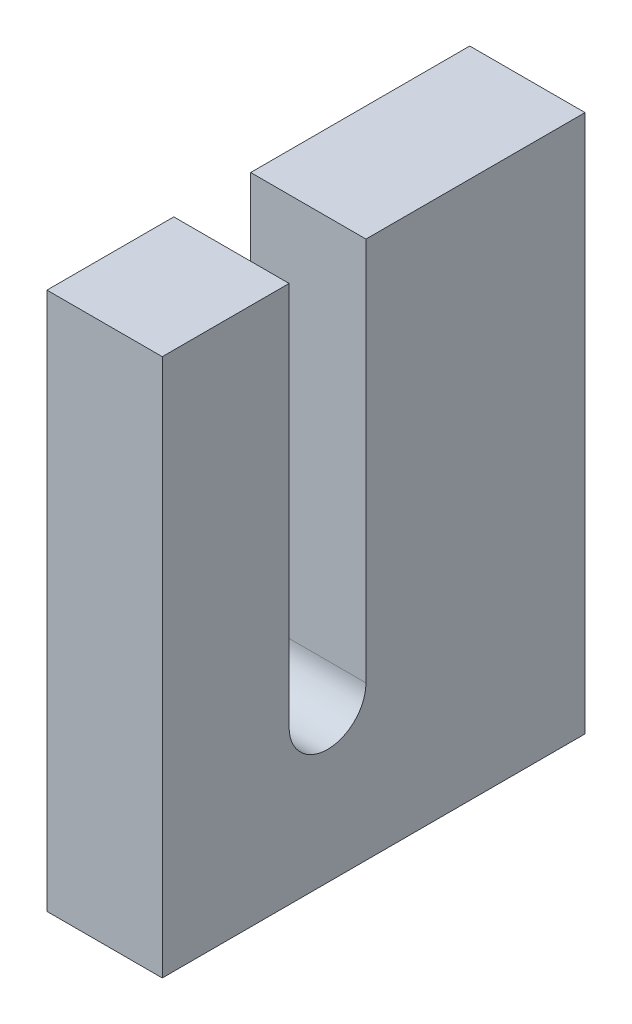
SolidWorks part; units mm, degrees
ref_plane "Plan de face" through (0, 0, 0) normal (0, 0, 1) x (1, 0, 0)
ref_plane "Plan de dessus" through (0, 0, 0) normal (0, 1, 0) x (1, 0, 0)
ref_plane "Plan de droite" through (0, 0, 0) normal (1, 0, 0) x (0, 0, -1)
sketch "Esquisse1" plane through (0, 0, 0) normal (0, 1, 0) x (1, 0, 0)
  line L1 (-7.5, -27.5) -> (7.5, -27.5)
  line L2 (-7.5, -27.5) -> (-7.5, 27.5)
  line L3 (-7.5, 27.5) -> (7.5, 27.5)
  line L4 (7.5, -27.5) -> (7.5, 27.5)
  line L5 (-7.5, -27.5) -> (7.5, 27.5) construction
  line L6 (-7.5, 27.5) -> (7.5, -27.5) construction
  point P0 (0, 0)
  dimension "D1" = 15
  dimension "D2" = 55
extrude "Boss.-Extru.1" add sketch "Esquisse1" along normal blind 70
sketch "Esquisse3" plane through (-7.5, 0, 0) normal (-1, 0, 0) x (0, 0, 1)
  line L0 (27.5, 70) -> (6, 70)
  line L1 (-27.5, 70) -> (27.5, 70) construction
  line L2 (6, 70) -> (6, 20)
  line L3 (1, 20) -> (1, 70)
  line L4 (11, 20) -> (11, 70)
  circle A0 centre (6, 20) radius 5
  dimension "D3" = 10
  dimension "D1" = 21.5
  dimension "D2" = 50
extrude "Enlèv. mat.-Extru.1" cut sketch "Esquisse3" against normal blind 45
